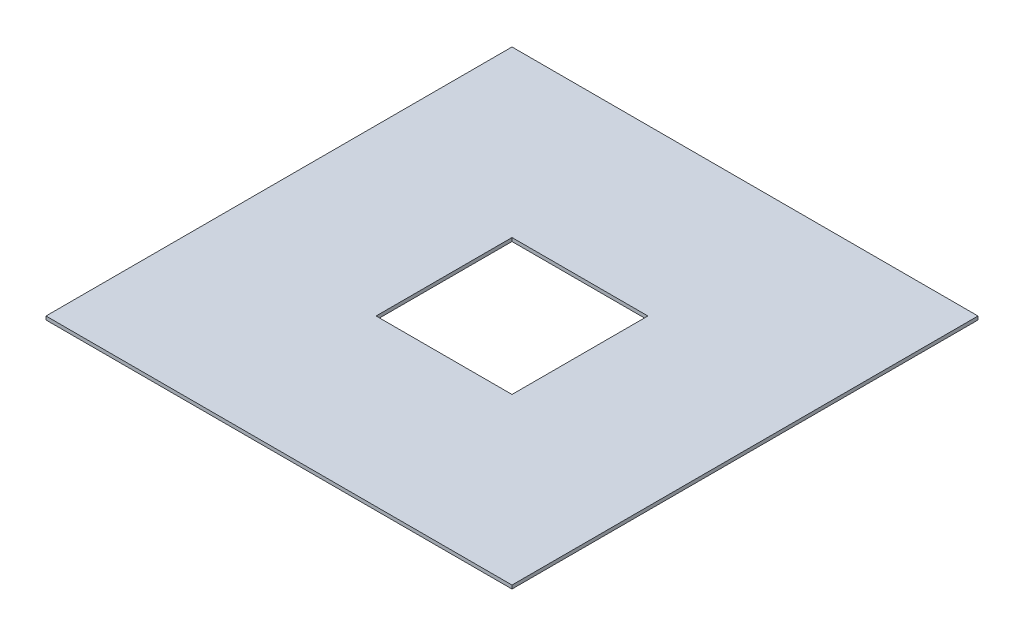
SolidWorks part; units mm, degrees
ref_plane "Front Plane" through (0, 0, 0) normal (0, 0, 1) x (1, 0, 0)
ref_plane "Top Plane" through (0, 0, 0) normal (0, 1, 0) x (1, 0, 0)
ref_plane "Right Plane" through (0, 0, 0) normal (1, 0, 0) x (0, 0, -1)
ref_plane "Plane1" through (0, 3.2338, 0) normal (0, 1, 0) x (1, 0, 0)
sketch "Sketch1" plane through (0, 3.2338, 0) normal (0, 1, 0) x (1, 0, 0)
  line L1 (-1.2, 1.2) -> (1.2, 1.2)
  line L2 (-1.2, 1.2) -> (-1.2, -1.2)
  line L3 (-1.2, -1.2) -> (1.2, -1.2)
  line L4 (1.2, 1.2) -> (1.2, -1.2)
  line L5 (-1.2, 1.2) -> (1.2, -1.2) construction
  line L6 (-1.2, -1.2) -> (1.2, 1.2) construction
  line L7 (-0.35, 0.35) -> (0.35, 0.35)
  line L8 (-0.35, 0.35) -> (-0.35, -0.35)
  line L9 (-0.35, -0.35) -> (0.35, -0.35)
  line L10 (0.35, 0.35) -> (0.35, -0.35)
  line L11 (-0.35, 0.35) -> (0.35, -0.35) construction
  line L12 (-0.35, -0.35) -> (0.35, 0.35) construction
  point P0 (0, 0)
  point P6 (0, 0)
  dimension "D1" = 2.4
  dimension "D2" = 2.4
  dimension "D3" = 0.7
  dimension "D4" = 0.7
extrude "Boss-Extrude1" add sketch "Sketch1" along normal blind 0.018
